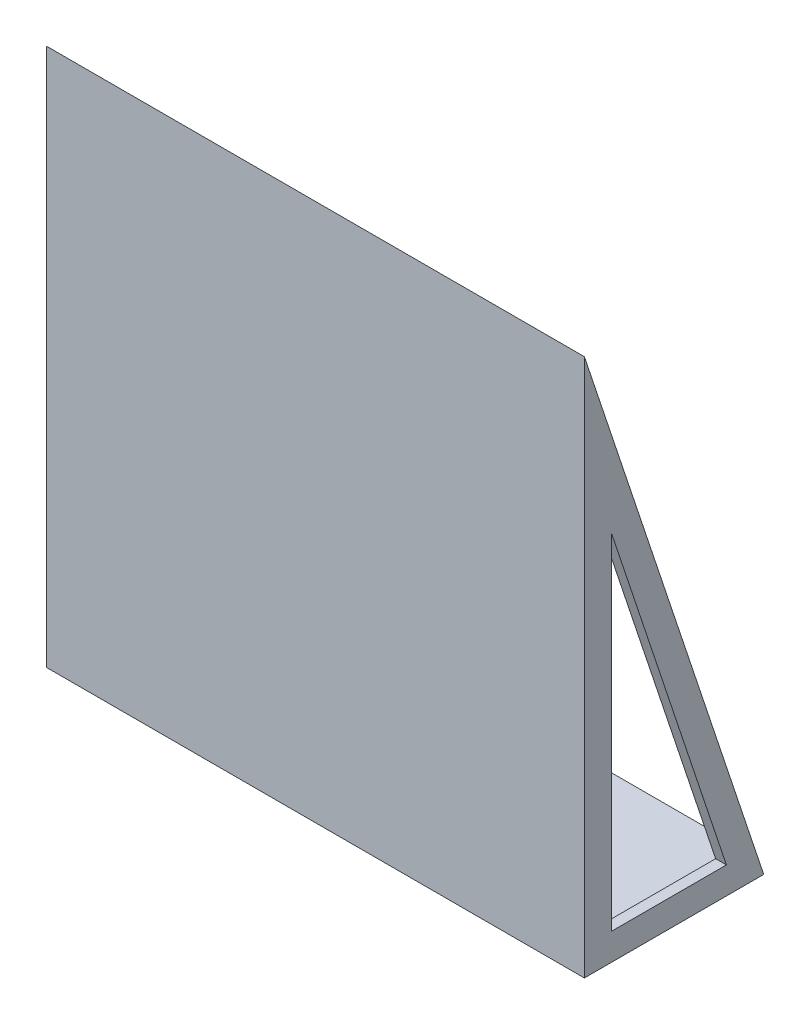
SolidWorks part; units mm, degrees
ref_plane "Front Plane" through (0, 0, 0) normal (0, 0, 1) x (1, 0, 0)
ref_plane "Top Plane" through (0, 0, 0) normal (0, 1, 0) x (1, 0, 0)
ref_plane "Right Plane" through (0, 0, 0) normal (1, 0, 0) x (0, 0, -1)
sketch "Sketch1" plane through (0, 0, 0) normal (0, 0, 1) x (1, 0, 0)
  line L1 (-150, 150) -> (150, 150)
  line L2 (-150, 150) -> (-150, -150)
  line L3 (-150, -150) -> (150, -150)
  line L4 (150, 150) -> (150, -150)
  line L5 (-150, 150) -> (150, -150) construction
  line L6 (-150, -150) -> (150, 150) construction
  point P0 (0, 0)
  dimension "D1" = 300
  dimension "D2" = 300
extrude "Boss-Extrude1" add sketch "Sketch1" against normal blind 100
sketch "Sketch3" plane through (-150, 0, 0) normal (-1, 0, 0) x (0, 0, 1)
  line L0 (-100, 150) -> (-100, -150)
  line L1 (-100, -150) -> (0, 150)
  line L2 (0, 150) -> (-100, 150)
sketch "Sketch4" plane through (0, 150, 0) normal (0, 1, 0) x (1, 0, 0)
  line L0 (150, 100) -> (-150, 100) construction
  line L1 (-144, 100) -> (144, 100)
  line L2 (-144, 100) -> (-144, 6)
  line L3 (-144, 6) -> (144, 6)
  line L4 (144, 100) -> (144, 6)
  line L5 (-150, 0) -> (-150, 100) construction
  line L6 (150, 100) -> (150, 0) construction
  line L7 (150, 0) -> (-150, 0) construction
  dimension "D1" = 6
  dimension "D2" = 6
  dimension "D3" = 6
extrude "Cut-Extrude1" cut sketch "Sketch4" against normal blind 290
extrude "Cut-Extrude2" cut sketch "Sketch3" against normal blind 309.1
sketch "Sketch5" plane through (-150, 0, 0) normal (-1, 0, 0) x (0, 0, 1)
  line L0 (-15, -135) -> (-15, 57.5658)
  line L1 (-15, 57.5658) -> (-79.1886, -135)
  line L2 (-79.1886, -135) -> (-15, -135)
  line L3 (0, 150) -> (0, -150) construction
  line L4 (-100, -150) -> (0, -150) construction
  line L5 (-100, -150) -> (0, 150) construction
  point P7 (0, 0)
  point P8 (-10, 8.9888)
  point P9 (-73.8395, -140)
  point P10 (-10, 65.7161)
  point P11 (0, 0)
  point P12 (0, 0)
  dimension "D1" = 15
  dimension "D2" = 15
  dimension "D3" = 15
extrude "Cut-Extrude3" cut sketch "Sketch5" against normal blind 309.1
scale "Scale1" scale about origin uniform scaling yes scale factor 0.001
